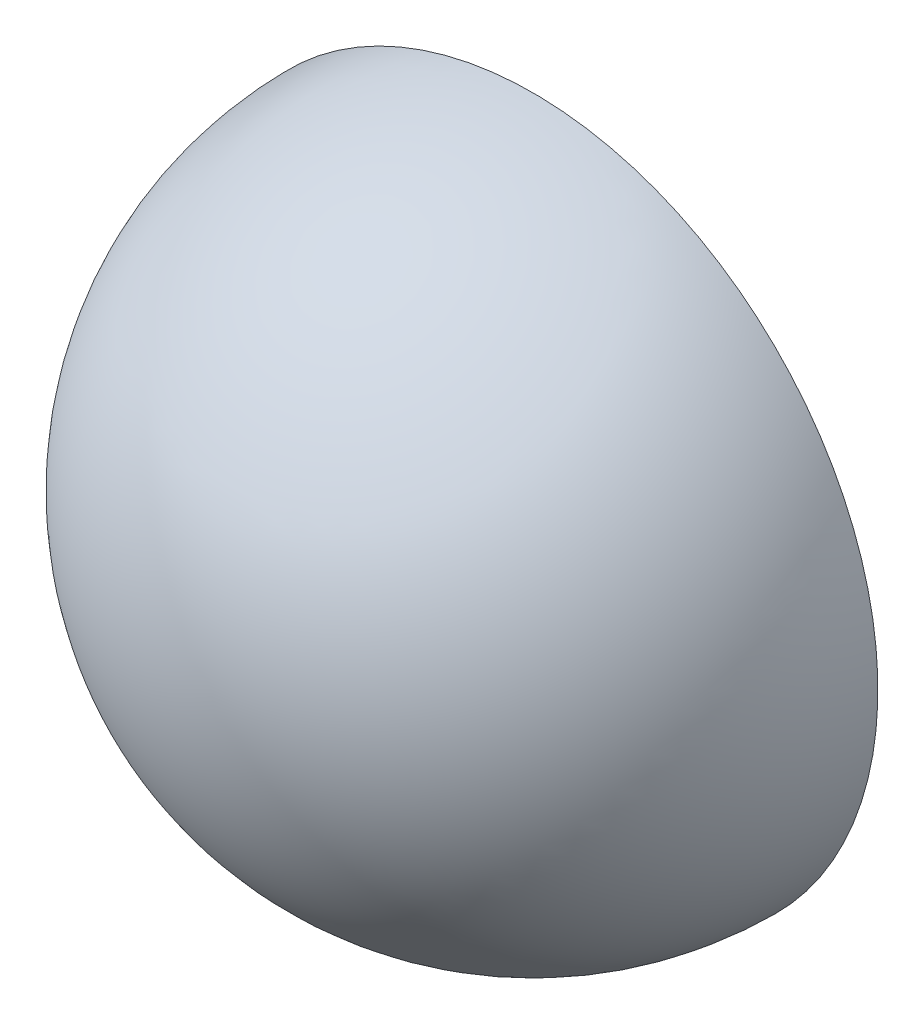
SolidWorks part; units mm, degrees
material "Настроенная пользователем пластмасса"
ref_plane "Спереди" through (0, 0, 0) normal (0, 0, 1) x (1, 0, 0)
ref_plane "Сверху" through (0, 0, 0) normal (0, 1, 0) x (1, 0, 0)
ref_plane "Справа" through (0, 0, 0) normal (1, 0, 0) x (0, 0, -1)
sketch "Эскиз1" plane through (0, 0, 0) normal (0, 1, 0) x (1, 0, 0)
  line L0 (0, 0) -> (0, -2)
  line L1 (0, 0) -> (-2, 0)
  line L2 (0, 0) -> (0, -5.1258) construction
  arc A0 (0, -2) -> (-2, 0) centre (0, 0) cw
  point P5 (0, -5.1258)
  point P6 (0, -2.6164)
  point P7 (0, 0.2891)
  point P8 (0, 0)
  dimension "D1" = 4
revolve "Повернуть1" add sketch "Эскиз1" angle 360 about L2
